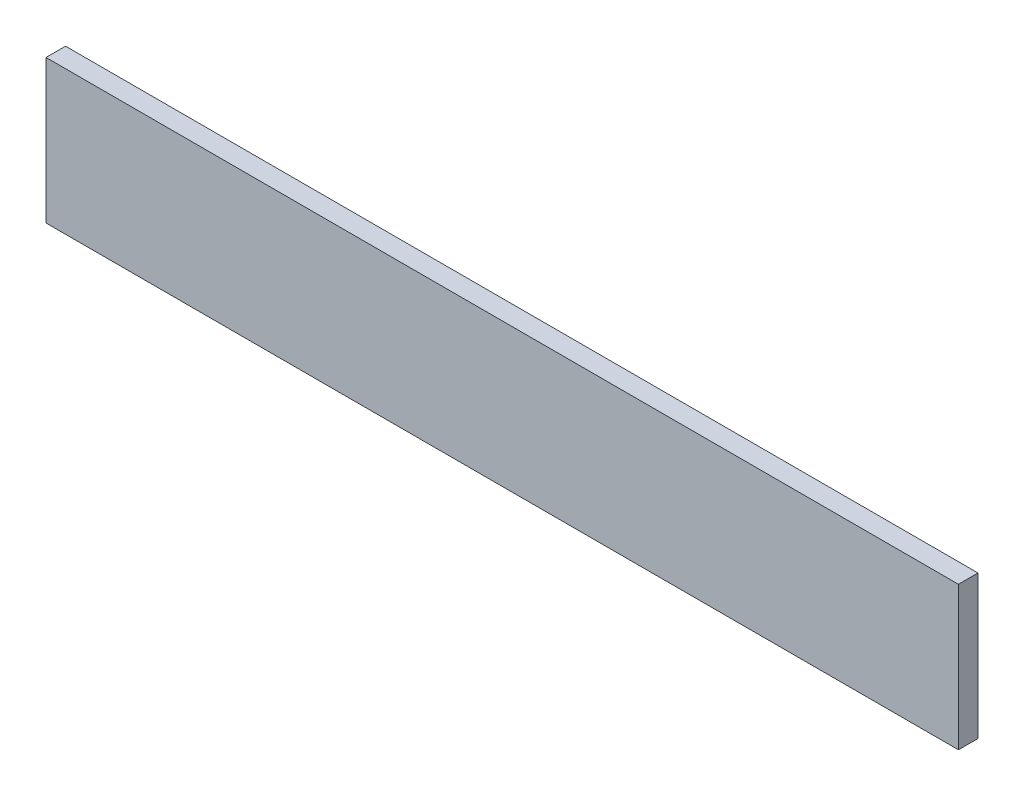
SolidWorks part; units mm, degrees
ref_plane "Front Plane" through (0, 0, 0) normal (0, 0, 1) x (1, 0, 0)
ref_plane "Top Plane" through (0, 0, 0) normal (0, 1, 0) x (1, 0, 0)
ref_plane "Right Plane" through (0, 0, 0) normal (1, 0, 0) x (0, 0, -1)
sketch "Sketch1" plane through (0, 0, 0) normal (0, 0, 1) x (1, 0, 0)
  line L1 (0, 0) -> (889, 0)
  line L2 (0, 0) -> (0, 139.7)
  line L3 (0, 139.7) -> (889, 139.7)
  line L4 (889, 0) -> (889, 139.7)
  dimension "D1" = 889
  dimension "D2" = 139.7
extrude "Boss-Extrude1" add sketch "Sketch1" along normal blind 19.05
